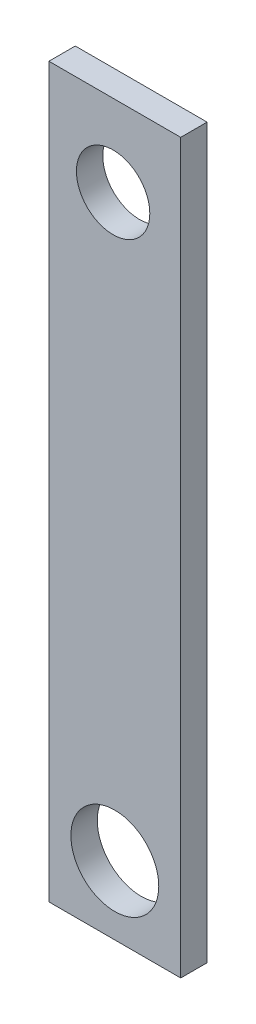
SolidWorks part; units mm, degrees
material "Copper"
ref_plane "Front Plane" through (0, 0, 0) normal (0, 0, 1) x (1, 0, 0)
ref_plane "Top Plane" through (0, 0, 0) normal (0, 1, 0) x (1, 0, 0)
ref_plane "Right Plane" through (0, 0, 0) normal (1, 0, 0) x (0, 0, -1)
sketch "Sketch1" plane through (0, 0, 0) normal (0, 0, 1) x (1, 0, 0)
  line L1 (-18.5554, -18.232) -> (-3.5554, -18.232)
  line L2 (-18.5554, -18.232) -> (-18.5554, -101.0831)
  line L3 (-18.5554, -101.0831) -> (-3.5554, -101.0831)
  line L4 (-3.5554, -18.232) -> (-3.5554, -101.0831)
  line L5 (-11.0554, -101.0831) -> (-11.0554, -18.232) construction
  circle A1 centre (-11.0554, -93.2869) radius 5
  circle A2 centre (-11.25, -27.5) radius 4.1769
  dimension "D2" = 10
  dimension "D1" = 15
extrude "Boss-Extrude1" add sketch "Sketch1" along normal blind 3
